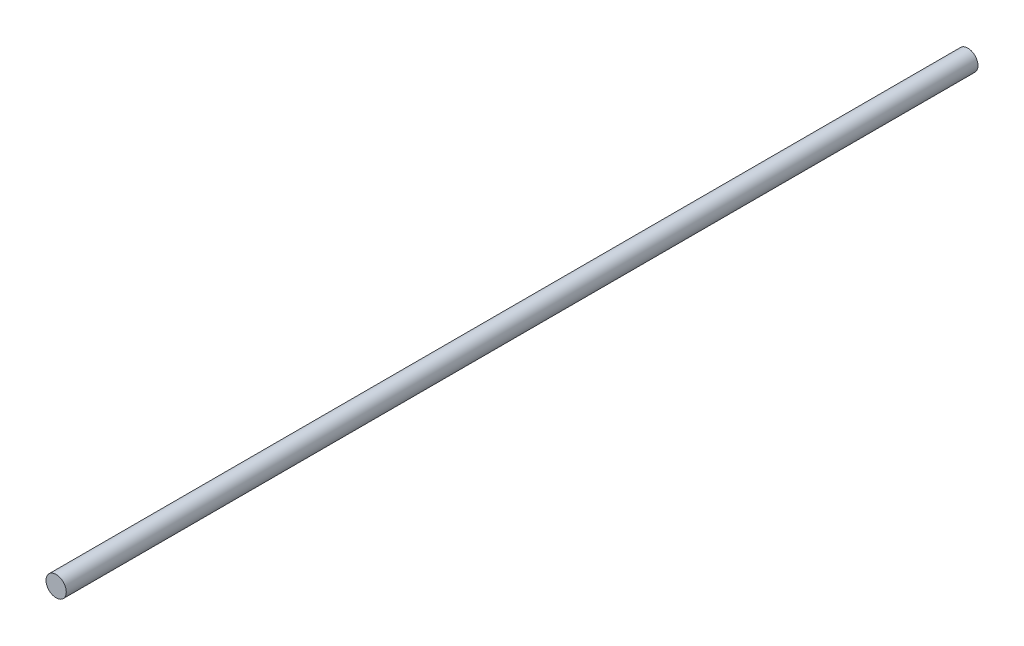
SolidWorks part; units mm, degrees
ref_plane "Front Plane" through (0, 0, 0) normal (0, 0, 1) x (1, 0, 0)
ref_plane "Top Plane" through (0, 0, 0) normal (0, 1, 0) x (1, 0, 0)
ref_plane "Right Plane" through (0, 0, 0) normal (1, 0, 0) x (0, 0, -1)
sketch "Sketch1" plane through (0, 0, 0) normal (0, 0, 1) x (1, 0, 0)
  circle A0 centre (0, 0) radius 5
extrude "Boss-Extrude1" add sketch "Sketch1" along normal blind 449
